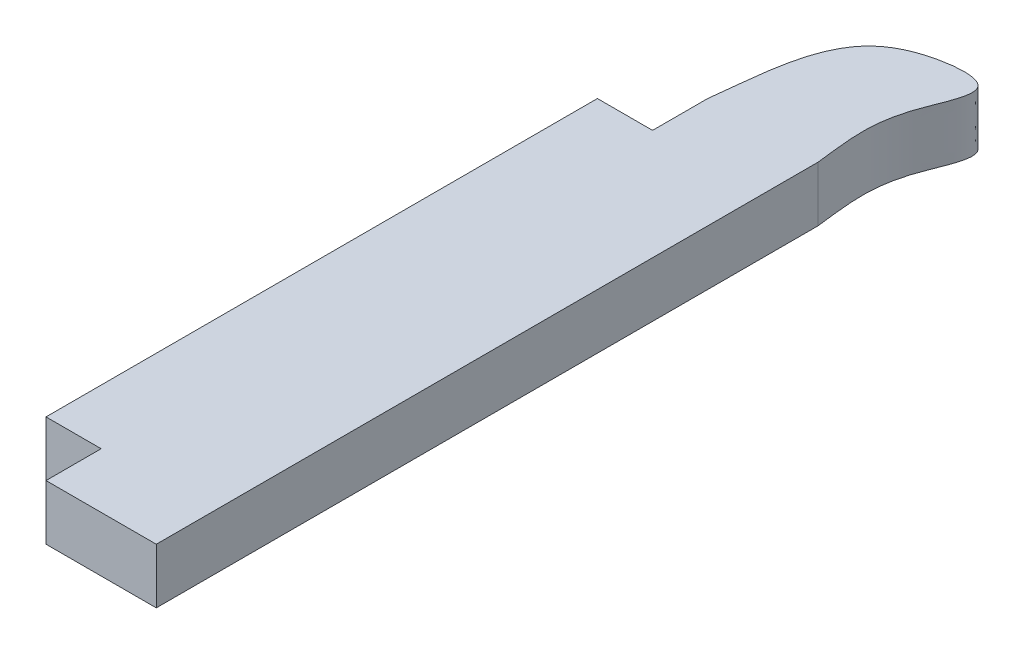
SolidWorks part; units mm, degrees
ref_plane "Front Plane" through (0, 0, 0) normal (0, 0, 1) x (1, 0, 0)
ref_plane "Top Plane" through (0, 0, 0) normal (0, 1, 0) x (1, 0, 0)
ref_plane "Right Plane" through (0, 0, 0) normal (1, 0, 0) x (0, 0, -1)
sketch "Sketch1" plane through (0, 0, 0) normal (0, 1, 0) x (1, 0, 0)
  line L0 (0, 0) -> (-6.35, 0)
  line L1 (6.35, -15.875) -> (-6.35, -15.875)
  line L2 (6.35, -15.875) -> (6.35, 15.875)
  line L3 (6.35, 15.875) -> (-6.35, 15.875)
  line L4 (-6.35, -15.875) -> (-6.35, 15.875)
  line L5 (6.35, -15.875) -> (-6.35, 15.875) construction
  line L6 (6.35, 15.875) -> (-6.35, -15.875) construction
  line L7 (-3.175, 15.875) -> (3.175, 15.875)
  line L8 (-3.175, 15.875) -> (-3.175, 19.05)
  line L9 (-3.175, 19.05) -> (3.175, 19.05)
  line L10 (3.175, 15.875) -> (3.175, 19.05)
  line L11 (3.175, -15.875) -> (3.175, -19.05)
  line L12 (-3.175, -19.05) -> (3.175, -19.05)
  line L13 (-3.175, -15.875) -> (-3.175, -19.05)
  spline S0 degree 3 poles (-3.175, 19.05) (-2.89, 21.1315) (-2.845, 25.5907) (0.8417, 27.7038) (5.0355, 28.0466) (2.5343, 23.2834) (2.9474, 21.0616) (3.175, 19.05) knots 0 0 0 0 0.335744 0.477587 0.606965 0.742564 1 1 1 1
  point P0 (0, 0)
  dimension "D1" = 31.75
  dimension "D2" = 12.7
  dimension "D3" = 3.175
  dimension "D4" = 6.35
  dimension "D5" = 3.175
extrude "Boss-Extrude1" add sketch "Sketch1" along normal blind 3.175
sketch "Sketch2" plane through (0, 3.175, 0) normal (0, 1, 0) x (1, 0, 0)
  line L1 (6.35, 15.875) -> (3.175, 15.875)
  line L2 (6.35, 15.875) -> (6.35, -34.925)
  line L3 (6.35, -34.925) -> (3.175, -34.925)
  line L4 (3.175, 15.875) -> (3.175, -34.925)
  dimension "D1" = 3.175
  dimension "D2" = 50.8
extrude "Cut-Extrude1" cut sketch "Sketch2" against normal through all
